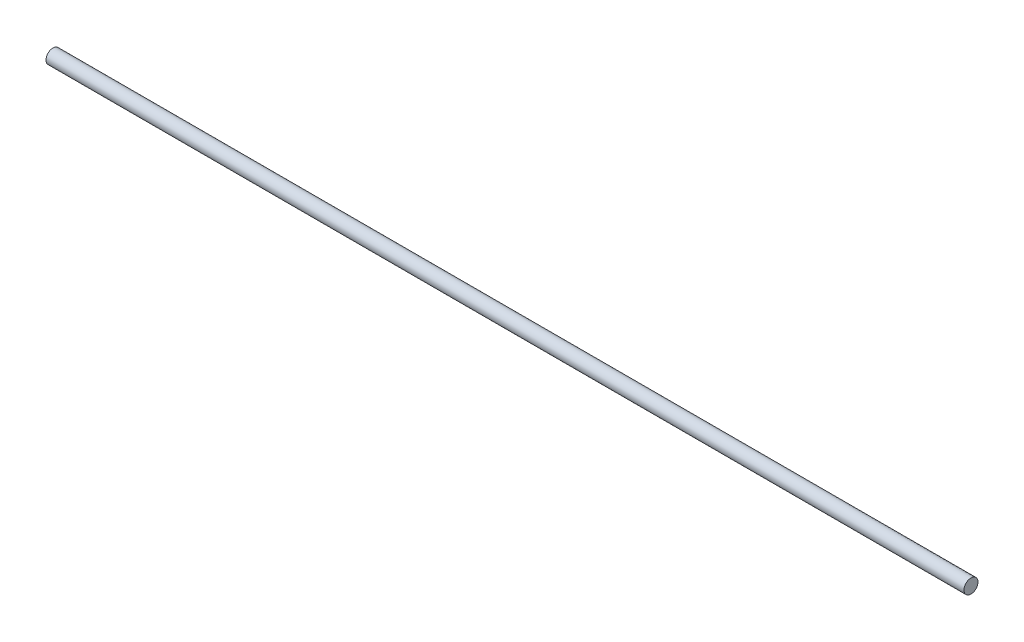
SolidWorks part; units mm, degrees
material "AISI Type 316L stainless steel"
ref_plane "Front Plane" through (0, 0, 0) normal (0, 0, 1) x (1, 0, 0)
ref_plane "Top Plane" through (0, 0, 0) normal (0, 1, 0) x (1, 0, 0)
ref_plane "Right Plane" through (0, 0, 0) normal (1, 0, 0) x (0, 0, -1)
sketch "Sketch1" plane through (0, 0, 0) normal (1, 0, 0) x (0, 0, -1)
  circle A0 centre (0, 0) radius 4
  dimension "D1" = 8
extrude "Boss-Extrude1" add sketch "Sketch1" along normal mid plane 523.8
